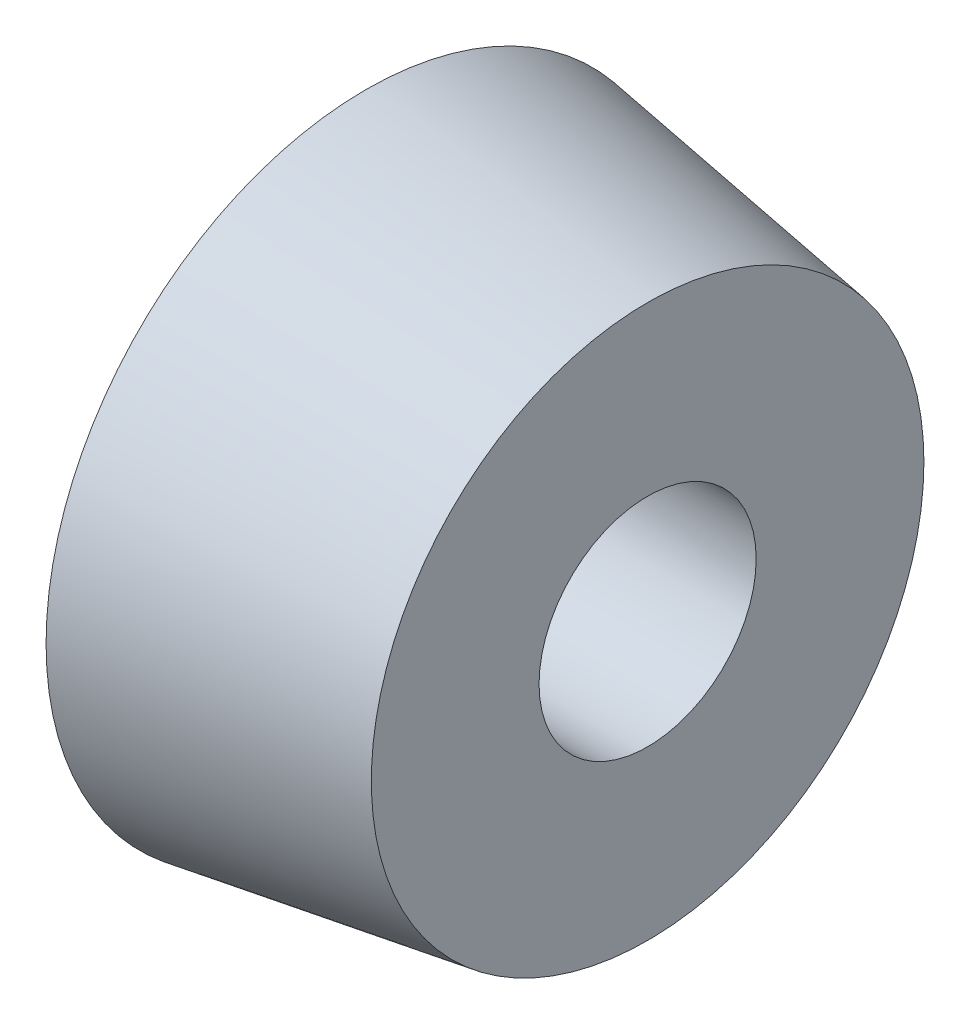
SolidWorks part; units mm, degrees
ref_plane "Front Plane" through (0, 0, 0) normal (0, 0, 1) x (1, 0, 0)
ref_plane "Top Plane" through (0, 0, 0) normal (0, 1, 0) x (1, 0, 0)
ref_plane "Right Plane" through (0, 0, 0) normal (1, 0, 0) x (0, 0, -1)
sketch "Sketch1" plane through (0, 0, 0) normal (0, 1, 0) x (1, 0, 0)
  line L2 (929.7723, 97.8305) -> (929.7723, 76.2)
  line L3 (948.8223, 94.8858) -> (948.8223, 76.2)
  line L4 (929.7723, 97.8305) -> (948.8223, 94.8858)
  line L5 (1049.7211, 76.2) -> (927.1762, 76.2) construction
  line L6 (929.7723, 76.2) -> (948.8223, 76.2)
  spline S0 degree 3 poles (1698.8541, -566.5092) (1513.356, -28.2517) (1211.581, 58.1372) (887.8186, 103.8771) (872.5346, 105.9273) (841.9435, 109.8647) (826.6361, 111.7515) (796.0038, 115.3893) (780.6789, 117.14) (734.683, 122.2143) (703.9913, 125.362) (642.5687, 131.261) (611.8375, 134.0115) (550.3439, 139.1405) (519.5815, 141.5188) (458.0303, 145.8934) (427.2415, 147.8905) (381.0416, 150.5596) (365.6389, 151.3944) (334.8283, 152.9394) (319.4206, 153.6499) (288.6013, 154.919) (273.1897, 155.4794) (250.0725, 156.1593) (242.3667, 156.3596) (230.8108, 156.6017) (226.9593, 156.6726) (99.3596, 158.5747) (-23.9566, 150.7789) (346.5117, -833.9102) knots -1.200454 -1.200454 -1.200454 -1.200454 0.0625 0.0625 0.125 0.125 0.1875 0.1875 0.25 0.25 0.375 0.375 0.5 0.5 0.625 0.625 0.75 0.75 0.8125 0.8125 0.875 0.875 0.9375 0.9375 0.96875 0.96875 0.984375 0.984375 1.48656 1.48656 1.48656 1.48656 only from (948.8223, 94.8858) to (211.5741, 156.845) construction
  spline S1 degree 3 poles (948.8223, 94.8858) (933.6019, 97.3018) (918.3518, 99.5635) (887.8186, 103.8771) (872.5346, 105.9273) (841.9435, 109.8647) (826.6361, 111.7515) (796.0038, 115.3893) (780.6789, 117.14) (734.683, 122.2143) (703.9913, 125.362) (642.5687, 131.261) (611.8375, 134.0115) (550.3439, 139.1405) (519.5815, 141.5188) (458.0303, 145.8934) (427.2415, 147.8905) (381.0416, 150.5596) (365.6389, 151.3944) (334.8283, 152.9394) (319.4206, 153.6499) (288.6013, 154.919) (273.1897, 155.4794) (250.0725, 156.1593) (242.3667, 156.3596) (230.8108, 156.6017) (226.9593, 156.6726) (219.2586, 156.7873) (215.4087, 156.8354) (211.5741, 156.845) knots 0 0 0 0 0.0625 0.0625 0.125 0.125 0.1875 0.1875 0.25 0.25 0.375 0.375 0.5 0.5 0.625 0.625 0.75 0.75 0.8125 0.8125 0.875 0.875 0.9375 0.9375 0.96875 0.96875 0.984375 0.984375 1 1 1 1 construction
  point P5 (1049.7211, 76.2)
  dimension "D1" = 19.05
revolve "Revolve2" add sketch "Sketch1" angle 360 about L5
hole_wizard "Tapped Hole for 9/16-12 Helicoil1" positions "Sketch2" profile "Sketch3" tap size "9/16-12" standard "Helicoil® Inch" end condition through all
sketch "Sketch2" plane through (929.7723, 0, 0) normal (-1, 0, 0) x (0, 0, 1)
  circle A3 centre (-76.2, 0) radius 21.6305
  circle A4 centre (-76.2, 0) radius 21.6305 construction
  point P0 (-76.2, 0)
  dimension "D1" = 0
cosmetic thread "Hole Thread1" parameters "D1"=19.05, "D2"=17.1475
sketch "Sketch3" plane through (929.7723, 0, -76.2) normal (0, 1, 0) x (0, 0, 1)
  line L0 (0, 0) -> (0, 19.05)
  line L1 (0, 19.05) -> (7.3419, 19.05)
  line L2 (7.3419, 19.05) -> (7.3419, 0)
  line L5 (7.3419, 0) -> (0, 0)
  line L11 (0, -6.35) -> (0, 107.95) construction
  dimension "Thru Tap Drill Dia." = 14.6837
  dimension "Thru Tap Drill Depth" = 19.05
sketch "Sketch4" plane through (929.7723, 0, 0) normal (-1, 0, 0) x (0, 0, 1)
  circle A0 centre (-76.2, 0) radius 10.3187
  circle A1 centre (-76.2, 0) radius 19.05
  dimension "D1" = 20.6375
  dimension "D2" = 38.1
extrude "Cut-Extrude1" [suppressed] cut sketch "Sketch4" against normal blind 12.7 draft 10
fillet "Fillet1" [suppressed] radius 3.175
sketch "Sketch5" plane through (0, 0, 0) normal (0, 1, 0) x (1, 0, 0)
  line L1 (927.6092, 95.5947) -> (927.6092, 86.0819)
  line L2 (927.6092, 95.5947) -> (943.5923, 93.1241)
  line L5 (946.2823, 89.9863) -> (946.2823, 89.2569)
  line L6 (943.1073, 86.0819) -> (927.6092, 86.0819)
  line L7 (948.8223, 94.8858) -> (929.7723, 97.8305) construction
  line L8 (948.8223, 94.8858) -> (929.7723, 97.8305) construction
  line L9 (948.8223, 83.5419) -> (929.7723, 83.5419) construction
  line L10 (948.8223, 83.5419) -> (929.7723, 83.5419) construction
  line L12 (1049.7211, 76.2) -> (913.4307, 76.2) construction
  arc A0 (946.2823, 89.2569) -> (943.1073, 86.0819) centre (943.1073, 89.2569) cw
  arc A1 (943.5923, 93.1241) -> (946.2823, 89.9863) centre (943.1073, 89.9863) cw
  point P14 (946.2823, 92.7083)
  dimension "D5" = 3.175
  dimension "D2" = 2.54
  dimension "D4" = 2.54
  dimension "D1" = 2.54
revolve "Cut-Revolve1" cut sketch "Sketch5" angle 360 about L12
